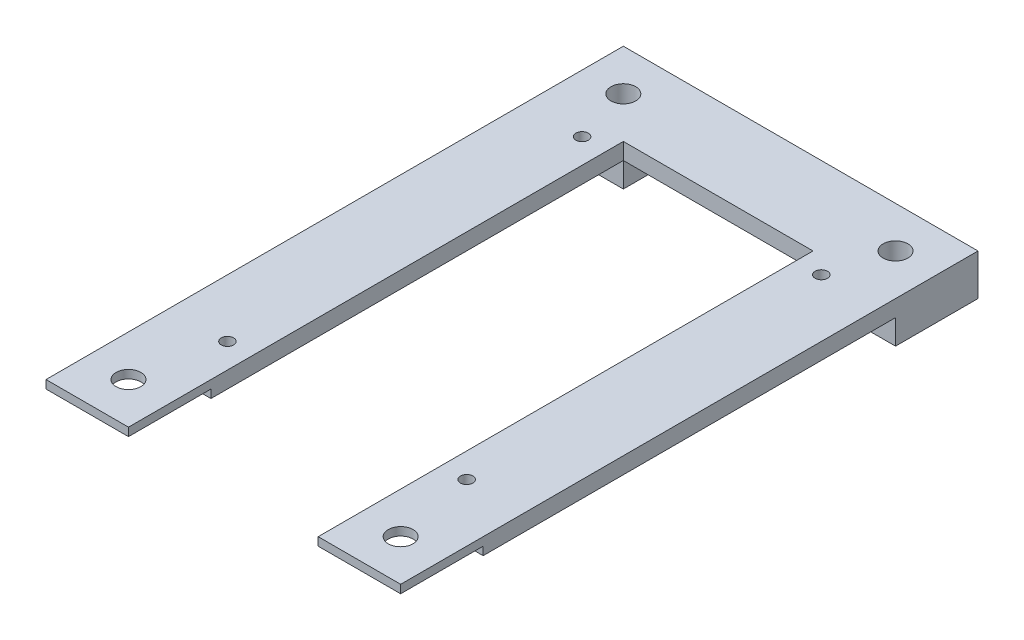
SolidWorks part; units mm, degrees
ref_plane "Front Plane" through (0, 0, 0) normal (0, 0, 1) x (1, 0, 0)
ref_plane "Top Plane" through (0, 0, 0) normal (0, 1, 0) x (1, 0, 0)
ref_plane "Right Plane" through (0, 0, 0) normal (1, 0, 0) x (0, 0, -1)
sketch "Sketch1" plane through (0, 0, 0) normal (0, 1, 0) x (1, 0, 0)
  line L0 (0, 0) -> (0, 140)
  line L1 (0, 140) -> (86, 140)
  line L2 (86, 140) -> (86, 0)
  line L3 (86, 0) -> (66, 0)
  line L4 (66, 0) -> (66, 120)
  line L5 (66, 120) -> (20, 120)
  line L6 (20, 120) -> (20, 0)
  line L7 (20, 0) -> (0, 0)
  circle A0 centre (10, 130) radius 3
  circle A1 centre (76, 130) radius 3
  point P3 (43, 140)
  dimension "D6" = 6
  dimension "D7" = 6
  dimension "D8" = 10
  dimension "D9" = 10
  dimension "D10" = 10
  dimension "D11" = 10
  dimension "D1" = 86
  dimension "D2" = 46
  dimension "D3" = 20
  dimension "D4" = 120
  dimension "D5" = 20
extrude "Boss-Extrude1" add sketch "Sketch1" along normal blind 4
sketch "Sketch2" plane through (0, 4, 0) normal (0, 1, 0) x (1, 0, 0)
  line L0 (20, 0) -> (20, 120) construction
  line L1 (0, 0) -> (20, 0) construction
  line L2 (66, 0) -> (86, 0) construction
  line L3 (66, 120) -> (66, 0) construction
  circle A0 centre (10, 10) radius 3
  circle A1 centre (76, 10) radius 3
  point P10 (76, 0)
  dimension "D1" = 6
  dimension "D2" = 6
  dimension "D3" = 10
  dimension "D5" = 10
  dimension "D6" = 10
  dimension "D4" = 10
extrude "Cut-Extrude1" cut sketch "Sketch2" against normal blind 4
sketch "Sketch3" plane through (0, 0, 0) normal (0, -1, 0) x (1, 0, 0)
  line L0 (0, -140) -> (86, -140)
  line L1 (66, -120) -> (86, -120)
  line L2 (86, 0) -> (86, -140) construction
  line L3 (86, -120) -> (86, -140)
  line L4 (20, -120) -> (0, -120)
  line L5 (0, -140) -> (0, 0) construction
  line L6 (20, -120) -> (66, -120)
  line L7 (0, -120) -> (0, -140)
  circle A0 centre (10, -130) radius 3
  circle A1 centre (76, -130) radius 3
extrude "Boss-Extrude2" add sketch "Sketch3" along normal blind 6
sketch "Sketch5" plane through (0, 0, 0) normal (0, 0, 1) x (1, 0, 0)
  line L0 (0, 4) -> (0, 0) construction
  line L1 (20, 0) -> (0, 0)
  line L2 (20, 0) -> (20, 2)
  line L3 (20, 2) -> (0, 2)
  line L4 (0, 0) -> (0, 2)
  line L5 (86, 4) -> (86, 0) construction
  line L6 (66, 0) -> (86, 0)
  line L7 (66, 0) -> (66, 2)
  line L8 (66, 2) -> (86, 2)
  line L9 (86, 0) -> (86, 2)
extrude "Cut-Extrude2" cut sketch "Sketch5" against normal blind 20
sketch "Sketch6" plane through (0, 4, 0) normal (0, 1, 0) x (1, 0, 0)
  line L0 (43, 140) -> (43, -9.7693) construction
  line L1 (86, 140) -> (0, 140) construction
  line L2 (0, 0) -> (20, 0) construction
  circle A0 centre (14, 30) radius 1.5
  circle A1 centre (14, 116) radius 1.5
  circle A2 centre (72, 116) radius 1.5
  circle A3 centre (72, 30) radius 1.5
  dimension "D1" = 29
  dimension "D2" = 3
  dimension "D3" = 29
  dimension "D4" = 3
  dimension "D5" = 86
  dimension "D6" = 30
extrude "Cut-Extrude3" cut sketch "Sketch6" against normal blind 20
sketch "Sketch7" plane through (0, 0, -120) normal (0, 0, 1) x (1, 0, 0)
  line L0 (86, -6) -> (0, -6) construction
  line L1 (20, 0) -> (66, 0)
  line L2 (20, 0) -> (20, -6)
  line L3 (20, -6) -> (66, -6)
  line L4 (66, 0) -> (66, -6)
extrude "Cut-Extrude4" cut sketch "Sketch7" against normal blind 20
